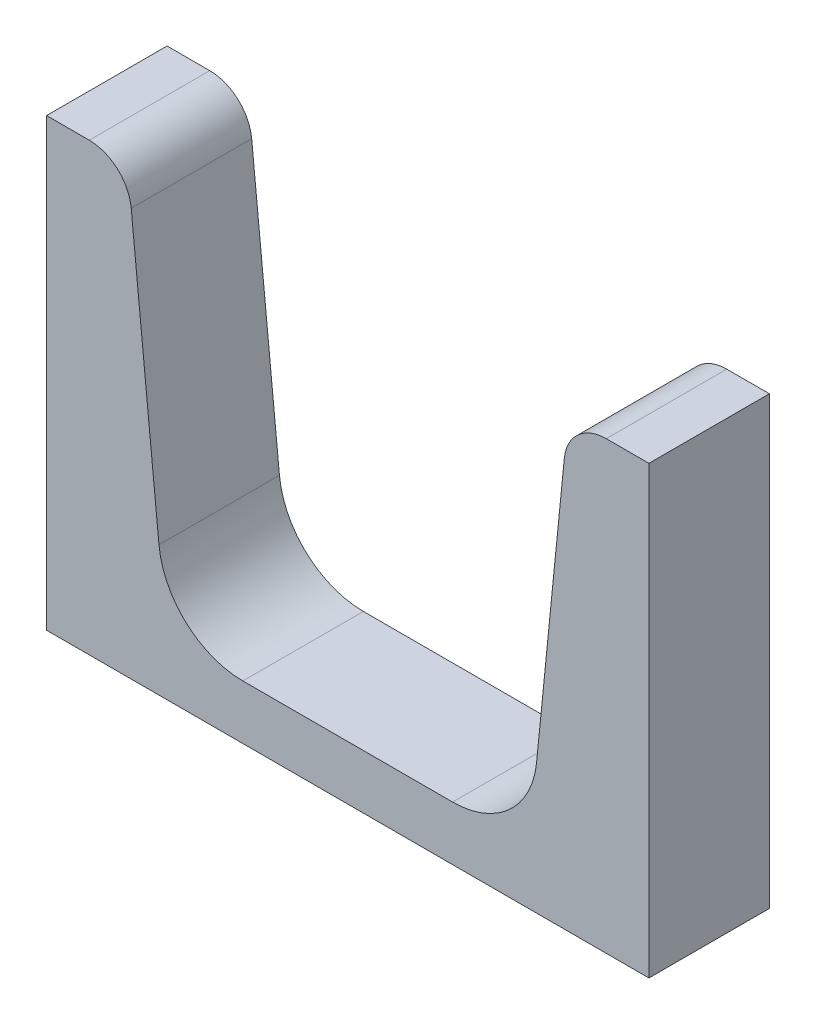
SolidWorks part; units mm, degrees
material "普通碳钢"
ref_plane "前视基准面" through (0, 0, 0) normal (0, 0, 1) x (1, 0, 0)
ref_plane "上视基准面" through (0, 0, 0) normal (0, 1, 0) x (1, 0, 0)
ref_plane "右视基准面" through (0, 0, 0) normal (1, 0, 0) x (0, 0, -1)
sketch "草图1" plane through (0, 0, 0) normal (0, 0, -1) x (-1, 0, 0)
  line L0 (0, 0) -> (0, 52.7004) construction
  line L1 (25, 0) -> (-25, 0)
  line L2 (-25, 0) -> (-25, 37)
  line L3 (-25, 37) -> (-18.2908, 37)
  line L4 (-18.2908, 37) -> (-15.0408, 4.5)
  line L5 (-15.0408, 4.5) -> (15.0408, 4.5)
  line L6 (18.2908, 37) -> (15.0408, 4.5)
  line L7 (25, 37) -> (18.2908, 37)
  line L8 (25, 0) -> (25, 37)
  line L9 (25, 20.75) -> (16.6658, 20.75) construction
  point P16 (0, 0)
  dimension "D1" = 50
  dimension "D2" = 37
  dimension "D3" = 4.5
  dimension "D4" = 8.3342
  dimension "D5" = 5.711
extrude "凸台-拉伸1" add sketch "草图1" against normal blind 10
fillet "圆角1" radius 3.5 2 edges at (-18.2908, 37, 5) (18.2908, 37, 5)
fillet "圆角2" radius 7 2 edges at (-15.0408, 4.5, 5) (15.0408, 4.5, 5)
